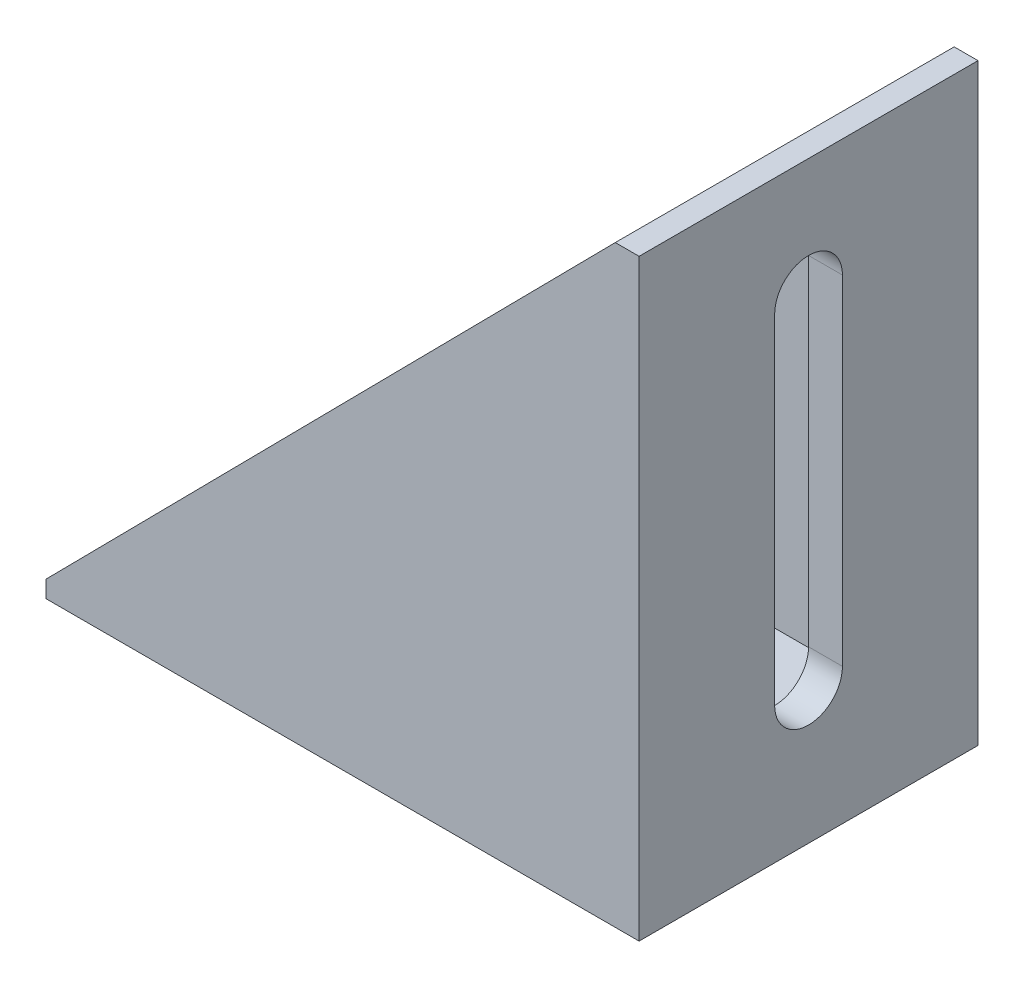
SolidWorks part; units mm, degrees
ref_plane "前视基准面" through (0, 0, 0) normal (0, 0, 1) x (1, 0, 0)
ref_plane "上视基准面" through (0, 0, 0) normal (0, 1, 0) x (1, 0, 0)
ref_plane "右视基准面" through (0, 0, 0) normal (1, 0, 0) x (0, 0, -1)
sketch "草图1" plane through (0, 0, 0) normal (0, 0, 1) x (1, 0, 0)
  line L0 (0, 0) -> (35, 0)
  line L1 (35, 0) -> (35, 35)
  line L2 (35, 35) -> (33.5942, 35)
  line L3 (0, 0) -> (0, 1)
  line L4 (33.5942, 35) -> (0, 1)
  dimension "D1" = 35
  dimension "D2" = 35
  dimension "D3" = 1
extrude "凸台-拉伸3" add sketch "草图1" along normal blind 10
sketch "草图4" plane through (0, 0, 10) normal (0, 0, 1) x (1, 0, 0)
  line L0 (3.7997, 2) -> (33, 2)
  line L1 (33, 2) -> (33, 31.553)
  line L2 (33.5942, 35) -> (0, 1) construction
  line L3 (0, 0) -> (35, 0) construction
  line L4 (35, 0) -> (35, 35) construction
  line L6 (33, 31.553) -> (33, 35.7838)
  line L7 (3.7997, 2) -> (-1.0576, 2)
  line L8 (-1.0576, 2) -> (33, 35.7838)
  dimension "D1" = 2
  dimension "D2" = 2
  dimension "D3" = 2
  dimension "D4" = 2
extrude "切除-拉伸2" cut sketch "草图4" against normal blind 8
sketch "草图7" plane through (0, 2, 0) normal (0, 1, 0) x (1, 0, 0)
  line L0 (7.6693, -10) -> (27.6693, -10) construction
  line L1 (0.9881, -10) -> (33, -10) construction
  line L2 (7.6693, -8) -> (27.6693, -8)
  line L3 (7.6693, -12) -> (27.6693, -12)
  arc A0 (7.6693, -8) -> (7.6693, -12) centre (7.6693, -10) ccw
  arc A1 (27.6693, -12) -> (27.6693, -8) centre (27.6693, -10) ccw
  point P4 (17.6693, -10)
  dimension "D1" = 20
  dimension "D2" = 4
extrude "切除-拉伸4" cut sketch "草图7" against normal blind 8
sketch "草图8" plane through (33, 0, 0) normal (-1, 0, 0) x (0, 0, 1)
  line L0 (10, 28.0426) -> (10, 8.0426) construction
  line L1 (10, 2) -> (10, 34.3986) construction
  line L2 (12, 28.0426) -> (12, 8.0426)
  line L3 (8, 28.0426) -> (8, 8.0426)
  arc A0 (12, 28.0426) -> (8, 28.0426) centre (10, 28.0426) ccw
  arc A1 (8, 8.0426) -> (12, 8.0426) centre (10, 8.0426) ccw
  point P4 (10, 18.0426)
  dimension "D1" = 20
  dimension "D2" = 4
extrude "切除-拉伸5" cut sketch "草图8" against normal blind 8
mirror "镜向3" about plane through (0, 35, 10) normal (0, 0, 1) of bodies 109
